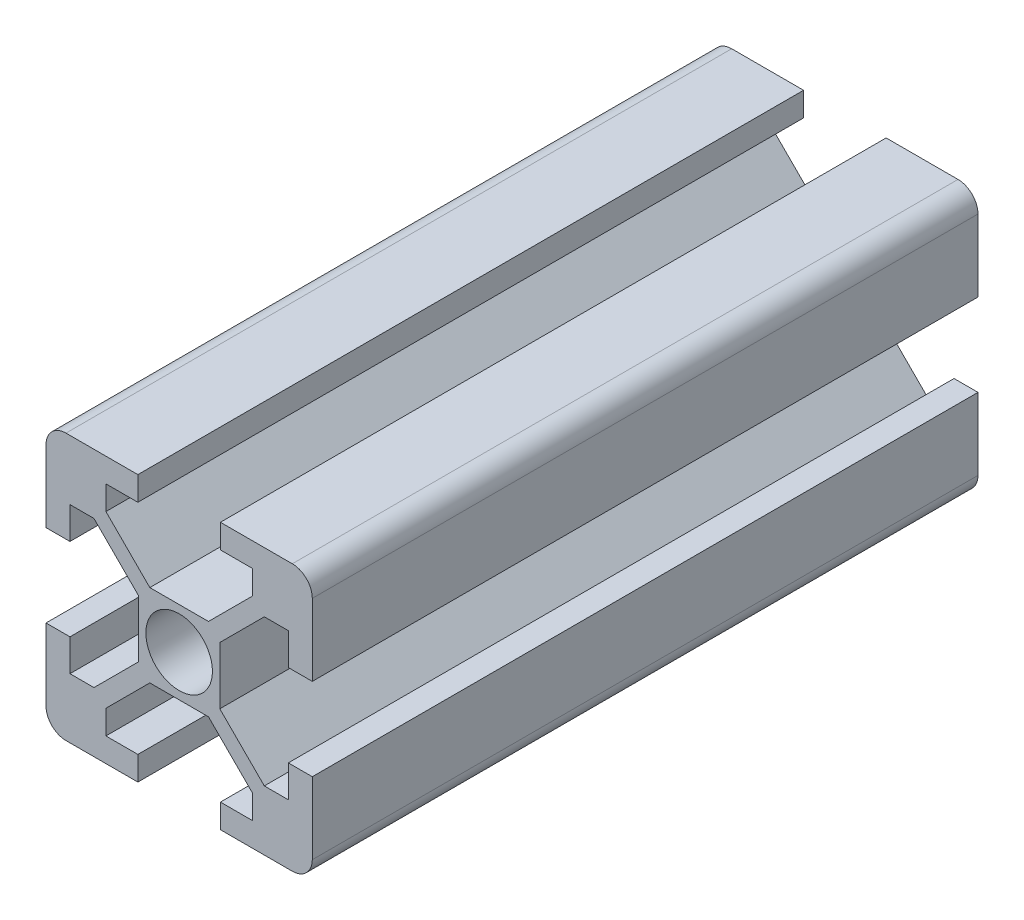
SolidWorks part; units mm, degrees
ref_plane "前视基准面" through (0, 0, 0) normal (0, 0, 1) x (1, 0, 0)
ref_plane "上视基准面" through (0, 0, 0) normal (0, 1, 0) x (1, 0, 0)
ref_plane "右视基准面" through (0, 0, 0) normal (1, 0, 0) x (0, 0, -1)
sketch "草图1" plane through (0, 0, 0) normal (0, 0, 1) x (1, 0, 0)
  line L0 (-10, -3.1) -> (-8.2, -3.1)
  line L1 (-8.5, 10) -> (8.5, 10)
  line L2 (-10, 8.5) -> (-10, -8.5)
  line L3 (-8.5, -10) -> (8.5, -10)
  line L4 (10, 8.5) -> (10, -8.5)
  line L5 (-10, 10) -> (10, -10) construction
  line L6 (-10, -10) -> (10, 10) construction
  line L7 (-3.0541, 3.1) -> (3.0541, 3.1)
  line L8 (-3.0541, 3.1) -> (-3.0541, -3.1)
  line L9 (-3.0541, -3.1) -> (3.0541, -3.1)
  line L10 (3.0541, 3.1) -> (3.0541, -3.1)
  line L11 (-3.0541, 3.1) -> (3.0541, -3.1) construction
  line L12 (-3.0541, -3.1) -> (3.0541, 3.1) construction
  line L13 (-8.2, -3.1) -> (-8.2, -5.5)
  line L14 (-8.2, -5.5) -> (-6.3971, -5.5)
  line L15 (-6.3971, -5.5) -> (-3.0541, -2.1571)
  line L16 (-5.5, 6.3971) -> (-2.1571, 3.0541)
  line L17 (-5.5, 8.2) -> (-5.5, 6.3971)
  line L18 (-3.1, 8.2) -> (-5.5, 8.2)
  line L19 (-3.1, 10) -> (-3.1, 8.2)
  line L20 (6.3971, 5.5) -> (3.0541, 2.1571)
  line L21 (8.2, 5.5) -> (6.3971, 5.5)
  line L22 (8.2, 3.1) -> (8.2, 5.5)
  line L23 (10, 3.1) -> (8.2, 3.1)
  line L24 (5.5, -6.3971) -> (2.1571, -3.0541)
  line L25 (5.5, -8.2) -> (5.5, -6.3971)
  line L26 (3.1, -8.2) -> (5.5, -8.2)
  line L27 (3.1, -10) -> (3.1, -8.2)
  line L28 (-3.1, -10) -> (-3.1, -8.2)
  line L29 (-3.1, -8.2) -> (-5.5, -8.2)
  line L30 (-5.5, -8.2) -> (-5.5, -6.3971)
  line L31 (-5.5, -6.3971) -> (-2.1571, -3.0541)
  line L32 (-8.2, 5.5) -> (-6.3971, 5.5)
  line L33 (-6.3971, 5.5) -> (-3.0541, 2.1571)
  line L34 (-8.2, 3.1) -> (-8.2, 5.5)
  line L35 (-10, 3.1) -> (-8.2, 3.1)
  line L36 (5.5, 8.2) -> (5.5, 6.3971)
  line L37 (5.5, 6.3971) -> (2.1571, 3.0541)
  line L38 (3.1, 8.2) -> (5.5, 8.2)
  line L39 (3.1, 10) -> (3.1, 8.2)
  line L40 (8.2, -5.5) -> (6.3971, -5.5)
  line L41 (6.3971, -5.5) -> (3.0541, -2.1571)
  line L42 (8.2, -3.1) -> (8.2, -5.5)
  line L43 (10, -3.1) -> (8.2, -3.1)
  circle A0 centre (0, 0) radius 2.5
  arc A1 (-10, 8.5) -> (-8.5, 10) centre (-8.5, 8.5) cw
  arc A2 (-10, -8.5) -> (-8.5, -10) centre (-8.5, -8.5) ccw
  arc A3 (8.5, 10) -> (10, 8.5) centre (8.5, 8.5) cw
  arc A4 (10, -8.5) -> (8.5, -10) centre (8.5, -8.5) cw
  point P0 (0, 0)
  point P20 (0, 0)
  point P26 (0, 0)
  point P32 (0, 0)
  point P38 (0, 0)
  point P60 (0, 0)
  dimension "D1" = 4
  dimension "D3" = 1.5
  dimension "D4" = 1.5
  dimension "D5" = 1.5
  dimension "D2" = 4
extrude "凸台-拉伸1" add sketch "草图1" along normal blind 50
